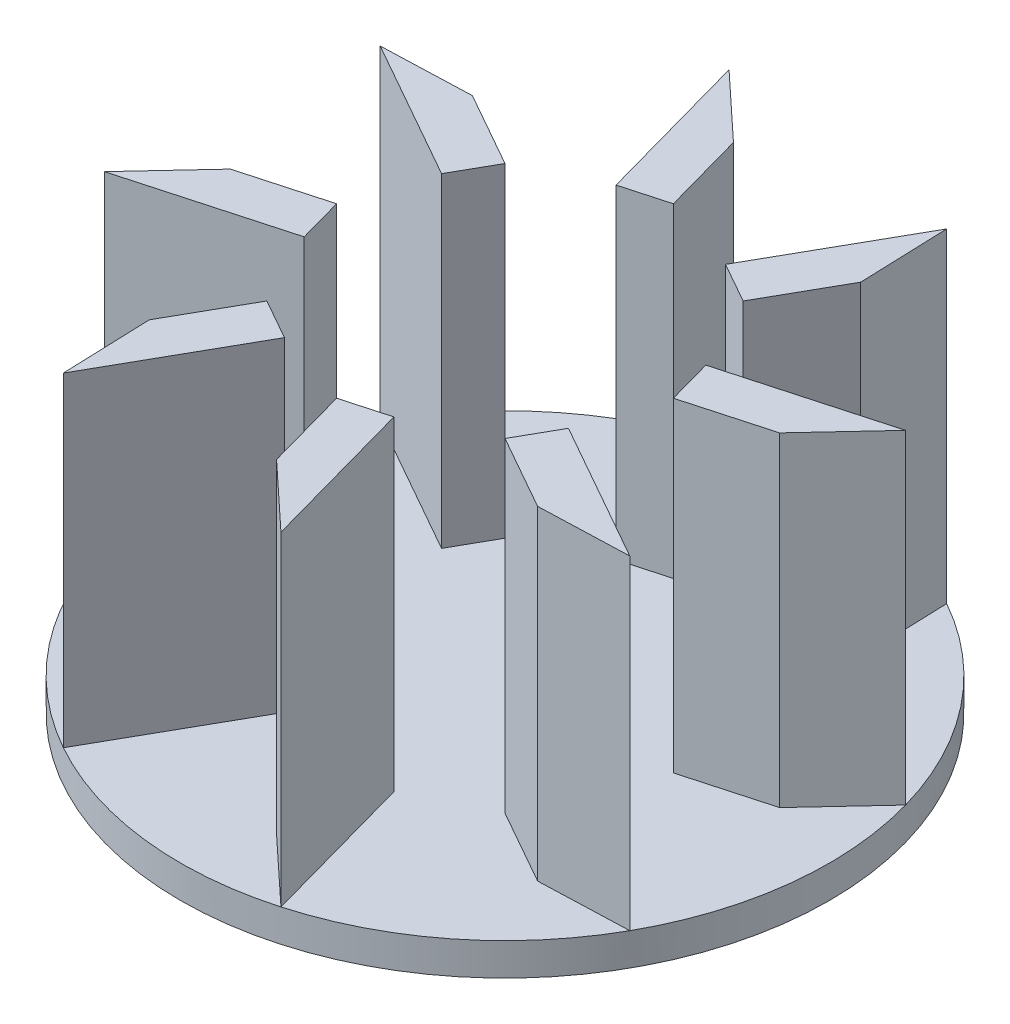
SolidWorks part; units mm, degrees
ref_plane "前视基准面" through (0, 0, 0) normal (0, 0, 1) x (1, 0, 0)
ref_plane "上视基准面" through (0, 0, 0) normal (0, 1, 0) x (1, 0, 0)
ref_plane "右视基准面" through (0, 0, 0) normal (1, 0, 0) x (0, 0, -1)
other "Configuration Table"
sketch "草图1" plane through (0, 0, 0) normal (0, 1, 0) x (1, 0, 0)
  circle A0 centre (0, 0) radius 20
extrude "凸台-拉伸1" add sketch "草图1" along normal blind 2
sketch "草图2" plane through (0, 2, 0) normal (0, 1, 0) x (1, 0, 0)
  line L0 (0, -23.0354) -> (0, 29.5369) construction
  line L1 (1.422, -15.5013) -> (0, -10.3778)
  line L2 (0, -10.3778) -> (2.7643, -9.6106)
  line L3 (2.7643, -9.6106) -> (5.4387, -19.2463)
  line L4 (5.4387, -19.2463) -> (1.422, -15.5013)
  line L5 (-9.9556, -11.9666) -> (-7.3382, -7.3382)
  line L6 (-7.3382, -7.3382) -> (-4.841, -8.7504)
  line L7 (-4.841, -8.7504) -> (-9.7634, -17.4549)
  line L8 (-9.7634, -17.4549) -> (-9.9556, -11.9666)
  line L9 (-15.5013, -1.422) -> (-10.3778, 0)
  line L10 (-10.3778, 0) -> (-9.6106, -2.7643)
  line L11 (-9.6106, -2.7643) -> (-19.2463, -5.4387)
  line L12 (-19.2463, -5.4387) -> (-15.5013, -1.422)
  line L13 (-11.9666, 9.9556) -> (-7.3382, 7.3382)
  line L14 (-7.3382, 7.3382) -> (-8.7504, 4.841)
  line L15 (-8.7504, 4.841) -> (-17.4549, 9.7634)
  line L16 (-17.4549, 9.7634) -> (-11.9666, 9.9556)
  line L17 (-1.422, 15.5013) -> (0, 10.3778)
  line L18 (0, 10.3778) -> (-2.7643, 9.6106)
  line L19 (-2.7643, 9.6106) -> (-5.4387, 19.2463)
  line L20 (-5.4387, 19.2463) -> (-1.422, 15.5013)
  line L21 (9.9556, 11.9666) -> (7.3382, 7.3382)
  line L22 (7.3382, 7.3382) -> (4.841, 8.7504)
  line L23 (4.841, 8.7504) -> (9.7634, 17.4549)
  line L24 (9.7634, 17.4549) -> (9.9556, 11.9666)
  line L25 (15.5013, 1.422) -> (10.3778, 0)
  line L26 (10.3778, 0) -> (9.6106, 2.7643)
  line L27 (9.6106, 2.7643) -> (19.2463, 5.4387)
  line L28 (19.2463, 5.4387) -> (15.5013, 1.422)
  line L29 (11.9666, -9.9556) -> (7.3382, -7.3382)
  line L30 (7.3382, -7.3382) -> (8.7504, -4.841)
  line L31 (8.7504, -4.841) -> (17.4549, -9.7634)
  line L32 (17.4549, -9.7634) -> (11.9666, -9.9556)
  circle A0 centre (0, 0) radius 20 construction
  point P40 (0, 0)
  dimension "D1" = 8
extrude "凸台-拉伸2" add sketch "草图2" along normal blind 20
